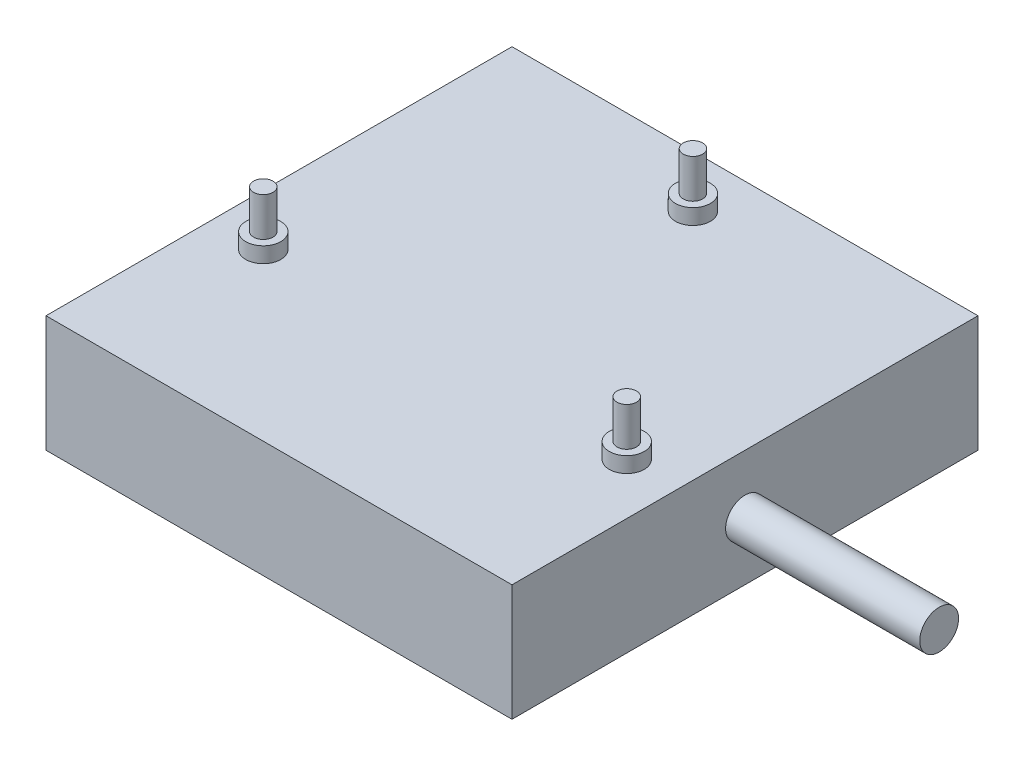
SolidWorks part; units mm, degrees
material "ABS"
ref_plane "Front Plane" through (0, 0, 0) normal (0, 0, 1) x (1, 0, 0)
ref_plane "Top Plane" through (0, 0, 0) normal (0, 1, 0) x (1, 0, 0)
ref_plane "Right Plane" through (0, 0, 0) normal (1, 0, 0) x (0, 0, -1)
sketch "Sketch1" plane through (0, 0, 0) normal (0, 1, 0) x (1, 0, 0)
  line L0 (-19.295, -19.171) -> (19.295, -19.171)
  line L5 (-30, -30) -> (30, 30) construction
  line L6 (-30, 30) -> (30, -30) construction
  line L7 (-19.295, -19.171) -> (-19.295, 19.171)
  line L8 (-19.295, 19.171) -> (19.295, 19.171)
  line L9 (19.295, -19.171) -> (19.295, 19.171)
  line L10 (-19.295, -19.171) -> (19.295, 19.171) construction
  line L11 (-19.295, 19.171) -> (19.295, -19.171) construction
  circle A0 centre (0, 23.296) radius 2.25
  circle A1 centre (23.4, -8.624) radius 2.25
  circle A2 centre (-23.4, -8.624) radius 2.25
  point P0 (0, 0)
  point P8 (0, 0)
  dimension "D1" = 60
  dimension "D2" = 60
  dimension "D3" = 0
  dimension "D4" = 23.4
  dimension "D5" = 23.4
  dimension "D6" = 23.296
  dimension "D7" = 8.624
  dimension "D8" = 8.624
  dimension "D9" = 23.4
  dimension "D10" = 38.59
  dimension "D11" = 38.342
sketch "Sketch2" plane through (0, 0, 0) normal (0, 1, 0) x (1, 0, 0)
  line L5 (-30, -30) -> (30, -30)
  line L6 (-30, -30) -> (-30, 30)
  line L7 (-30, 30) -> (30, 30)
  line L8 (30, -30) -> (30, 30)
  line L9 (-30, -30) -> (30, 30) construction
  line L10 (-30, 30) -> (30, -30) construction
  point P0 (0, 0)
  dimension "D1" = 60
  dimension "D2" = 60
extrude "Boss-Extrude1" add sketch "Sketch2" against normal blind 15
sketch "Sketch3" plane through (-30, 0, 0) normal (-1, 0, 0) x (0, 0, 1)
  line L0 (0, -7.5) -> (-19, -7.5)
  line L1 (-9.1477, -34.0177) -> (20.8523, -34.0177)
  line L2 (-4.5, -12.1904) -> (-4.5, -2.8096)
  line L3 (0, -7.5) -> (19, -7.5)
  line L4 (0, 0) -> (0, -15)
  line L5 (19.171, 0) -> (-19.171, 0) construction
  line L6 (-30, -15) -> (30, -15) construction
  line L7 (4.5, -12.1904) -> (4.5, -2.8096)
  line L8 (-16.4284, -4.5308) -> (-4.5, -2.8096)
  line L9 (-4.5, -12.1904) -> (-16.4284, -10.4692)
  line L10 (4.5, -2.8096) -> (16.4284, -4.5308)
  line L11 (4.5, -12.1904) -> (16.4284, -10.4692)
  circle A0 centre (0, -7.5) radius 6.5
  circle A1 centre (16, -7.5) radius 3
  circle A2 centre (-16, -7.5) radius 3
  circle A3 centre (0, -7.5) radius 4.5
  point P20 (-4.5, -7.5)
  point P23 (4.5, -7.5)
  dimension "D1" = 13
  dimension "D5" = 6
  dimension "D6" = 6
  dimension "D7" = 9
  dimension "D2" = 19
  dimension "D3" = 19
  dimension "D4" = 30
extrude "Cut-Extrude1" cut sketch "Sketch3" against normal blind 3 contours A2 L9 A0 L0 | L0 A2 | L0 A2 | A2 L0 A0 L8 | A3 L4 A0 L2 | L2 A0 L0 | L0 A0 L2 | A3 L2 A0 L4 | A3 L4 A0 L7 | L4 A3 L3 | L3 A3 L4 | L4 A3 L0 | L0 A3 L4 | A3 L7 A0 L4 | L3 A0 L7 | L7 A0 L3 | A1 L3 A0 L11 | A1 L10 A0 L3 | L3 A1 | L3 A1
extrude "Boss-Extrude2" add sketch "Sketch1" along normal blind 2 contours A2 | A0 | A1
sketch "Sketch4" plane through (0, 2, 0) normal (0, 1, 0) x (1, 0, 0)
  circle A0 centre (-23.4, -8.624) radius 1.25
  circle A2 centre (23.4, -8.624) radius 1.25
  circle A3 centre (0, 23.296) radius 1.25
  dimension "D1" = 2.5
  dimension "D2" = 2.5
  dimension "D3" = 2.5
extrude "Boss-Extrude3" add sketch "Sketch4" along normal blind 5
sketch "Sketch5" plane through (30, 0, 0) normal (1, 0, 0) x (0, 0, -1)
  line L0 (-30, -7.5) -> (30, -7.5)
  line L1 (-30, -15) -> (-30, 0) construction
  line L2 (30, -15) -> (30, 0) construction
  line L3 (0, -15) -> (0, 0)
  line L4 (-30, -15) -> (30, -15) construction
  circle A0 centre (0, -7.5) radius 2.5
  dimension "D1" = 5
extrude "Boss-Extrude4" add sketch "Sketch5" along normal blind 25 contours A0
ref_plane "Plane1" through (0, -7.5, 0) normal (0, 1, 0) x (1, 0, 0)
